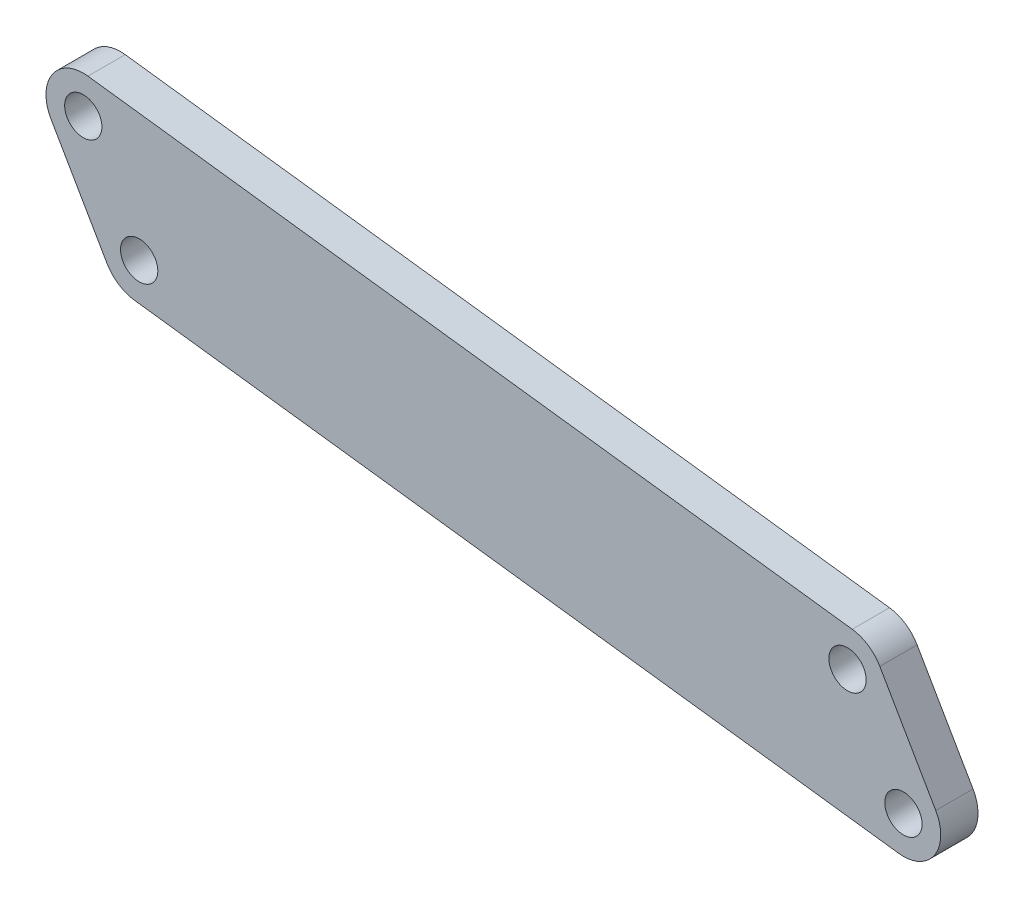
SolidWorks part; units mm, degrees
ref_plane "Front Plane" through (0, 0, 0) normal (0, 0, 1) x (1, 0, 0)
ref_plane "Top Plane" through (0, 0, 0) normal (0, 1, 0) x (1, 0, 0)
ref_plane "Right Plane" through (0, 0, 0) normal (1, 0, 0) x (0, 0, -1)
sketch "Sketch1" plane through (0, 0, 0) normal (0, 0, 1) x (1, 0, 0)
  line L0 (0, 0) -> (-57, 0)
  line L1 (-57, 0) -> (-61.5, 7.7942)
  line L2 (0, 0) -> (4.5, -7.7942)
  dimension "D1" = 57
  dimension "D2" = 9
  dimension "D3" = 9
  dimension "D4" = 120
  dimension "D5" = 120
sketch "Sketch2" plane through (0, 0, 0) normal (0, 0, 1) x (1, 0, 0)
  line L0 (-61.1228, 10.7704) -> (0.3772, 2.9762)
  line L1 (2.5981, 1.5) -> (7.0981, -6.2942)
  line L2 (4.1228, -10.7704) -> (-57.3772, -2.9762)
  line L3 (-59.5981, -1.5) -> (-64.0981, 6.2942)
  circle A0 centre (-57, 0) radius 1.5
  circle A1 centre (-61.5, 7.7942) radius 1.5
  arc A2 (-61.1228, 10.7704) -> (-64.0981, 6.2942) centre (-61.5, 7.7942) ccw
  arc A3 (-59.5981, -1.5) -> (-57.3772, -2.9762) centre (-57, 0) ccw
  circle A4 centre (0, 0) radius 1.5
  circle A5 centre (4.5, -7.7942) radius 1.5
  arc A6 (2.5981, 1.5) -> (0.3772, 2.9762) centre (0, 0) ccw
  arc A7 (4.1228, -10.7704) -> (7.0981, -6.2942) centre (4.5, -7.7942) ccw
  dimension "D1" = 3
  dimension "D2" = 3
  dimension "D3" = 3
  dimension "D4" = 3
  dimension "D5" = 6
  dimension "D6" = 6
  dimension "D7" = 6
  dimension "D8" = 6
extrude "Boss-Extrude1" add sketch "Sketch2" along normal blind 3
